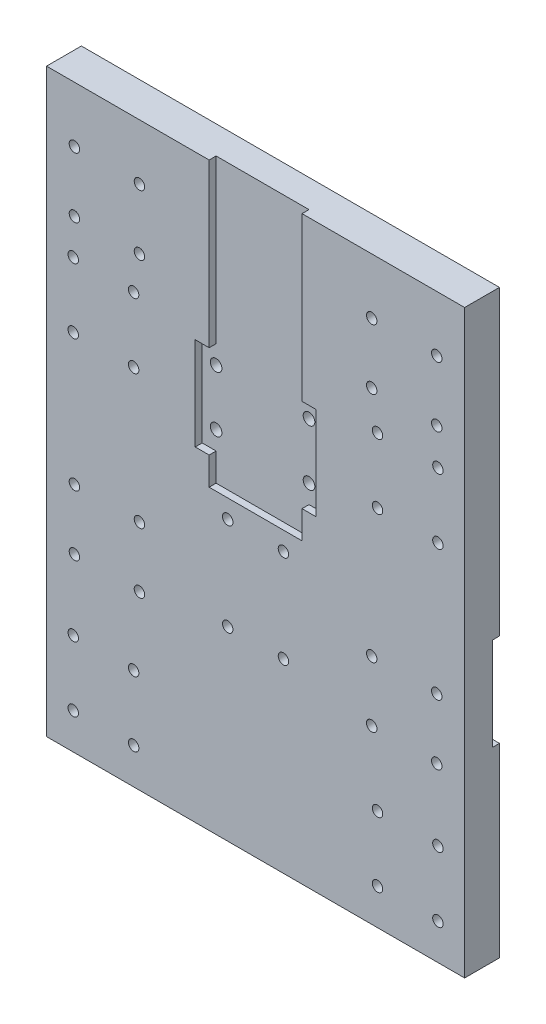
SolidWorks part; units mm, degrees
ref_plane "Plan de face" through (0, 0, 0) normal (0, 0, 1) x (1, 0, 0)
ref_plane "Plan de dessus" through (0, 0, 0) normal (0, 1, 0) x (1, 0, 0)
ref_plane "Plan de droite" through (0, 0, 0) normal (1, 0, 0) x (0, 0, -1)
sketch "Esquisse1" plane through (0, 0, 0) normal (0, 0, 1) x (1, 0, 0)
  line L1 (0, 0) -> (180, 0)
  line L2 (0, 0) -> (0, 250)
  line L3 (0, 250) -> (180, 250)
  line L4 (180, 0) -> (180, 250)
  dimension "D1" = 180
  dimension "D2" = 250
extrude "Boss.-Extru.1" add sketch "Esquisse1" along normal blind 15
sketch "Esquisse2" plane through (0, 0, 15) normal (0, 0, 1) x (1, 0, 0)
  line L0 (90, 0) -> (90, 250) construction
  line L1 (0, 0) -> (180, 0) construction
  line L2 (180, 250) -> (0, 250) construction
  line L3 (180, 100) -> (0, 100) construction
  line L4 (180, 0) -> (180, 250) construction
  line L5 (0, 250) -> (0, 0) construction
  line L6 (11.5, 156.5) -> (37.5, 156.5) construction
  line L7 (37.5, 156.5) -> (37.5, 184.5) construction
  line L8 (37.5, 184.5) -> (11.5, 184.5) construction
  line L9 (11.5, 184.5) -> (11.5, 156.5) construction
  line L10 (168.5, 184.5) -> (168.5, 156.5) construction
  line L11 (142.5, 184.5) -> (168.5, 184.5) construction
  line L12 (142.5, 156.5) -> (142.5, 184.5) construction
  line L13 (168.5, 156.5) -> (142.5, 156.5) construction
  line L14 (168.5, 43.5) -> (142.5, 43.5) construction
  line L15 (142.5, 43.5) -> (142.5, 15.5) construction
  line L16 (142.5, 15.5) -> (168.5, 15.5) construction
  line L17 (168.5, 15.5) -> (168.5, 43.5) construction
  line L18 (11.5, 15.5) -> (11.5, 43.5) construction
  line L19 (37.5, 15.5) -> (11.5, 15.5) construction
  line L20 (37.5, 43.5) -> (37.5, 15.5) construction
  line L21 (11.5, 43.5) -> (37.5, 43.5) construction
  line L39 (11.5, 141.5) -> (11.5, 156.5) construction
  circle A0 centre (11.5, 184.5) radius 2.25
  circle A1 centre (37.5, 184.5) radius 2.25
  circle A2 centre (37.5, 156.5) radius 2.25
  circle A3 centre (11.5, 156.5) radius 2.25
  circle A4 centre (168.5, 156.5) radius 2.25
  circle A5 centre (142.5, 156.5) radius 2.25
  circle A6 centre (142.5, 184.5) radius 2.25
  circle A7 centre (168.5, 184.5) radius 2.25
  circle A8 centre (168.5, 15.5) radius 2.25
  circle A9 centre (142.5, 15.5) radius 2.25
  circle A10 centre (142.5, 43.5) radius 2.25
  circle A11 centre (168.5, 43.5) radius 2.25
  circle A12 centre (11.5, 43.5) radius 2.25
  circle A13 centre (37.5, 43.5) radius 2.25
  circle A14 centre (37.5, 15.5) radius 2.25
  circle A15 centre (11.5, 15.5) radius 2.25
  circle A16 centre (78, 120) radius 2.25
  circle A17 centre (78, 80) radius 2.25
  circle A18 centre (102, 80) radius 2.25
  circle A19 centre (102, 120) radius 2.25
  dimension "D1" = 4.5
  dimension "D2" = 28
  dimension "D3" = 26
  dimension "D7" = 4.5
  dimension "D4" = 105
  dimension "D5" = 113
  dimension "D6" = 150
  dimension "D8" = 15
  dimension "D9" = 24
  dimension "D10" = 40
extrude "Enlèv. mat.-Extru.1" cut sketch "Esquisse2" against normal up to vertex (15 mm away) up to point (0, 250, 0)
sketch "Esquisse3" plane through (0, 0, 15) normal (0, 0, 1) x (1, 0, 0)
  line L0 (90, 0) -> (90, 250) construction
  line L1 (0, 0) -> (180, 0) construction
  line L2 (180, 250) -> (0, 250) construction
  line L3 (0, 150) -> (180, 150) construction
  line L4 (0, 250) -> (0, 0) construction
  line L5 (180, 0) -> (180, 250) construction
  line L6 (40, 200) -> (40, 226) construction
  line L7 (40, 226) -> (12, 226) construction
  line L8 (12, 226) -> (12, 200) construction
  line L9 (12, 200) -> (40, 200) construction
  line L10 (168, 200) -> (140, 200) construction
  line L11 (168, 226) -> (168, 200) construction
  line L12 (140, 226) -> (168, 226) construction
  line L13 (140, 200) -> (140, 226) construction
  line L14 (140, 100) -> (140, 74) construction
  line L15 (140, 74) -> (168, 74) construction
  line L16 (168, 74) -> (168, 100) construction
  line L17 (168, 100) -> (140, 100) construction
  line L18 (12, 100) -> (40, 100) construction
  line L19 (12, 74) -> (12, 100) construction
  line L20 (40, 74) -> (12, 74) construction
  line L21 (40, 100) -> (40, 74) construction
  circle A0 centre (12, 226) radius 2.25
  circle A1 centre (40, 226) radius 2.25
  circle A2 centre (12, 200) radius 2.25
  circle A3 centre (40, 200) radius 2.25
  circle A4 centre (11.5, 156.5) radius 2.25 construction
  circle A5 centre (140, 200) radius 2.25
  circle A6 centre (168, 200) radius 2.25
  circle A7 centre (140, 226) radius 2.25
  circle A8 centre (168, 226) radius 2.25
  circle A9 centre (168, 74) radius 2.25
  circle A10 centre (140, 74) radius 2.25
  circle A11 centre (168, 100) radius 2.25
  circle A12 centre (140, 100) radius 2.25
  circle A13 centre (40, 100) radius 2.25
  circle A14 centre (12, 100) radius 2.25
  circle A15 centre (40, 74) radius 2.25
  circle A16 centre (12, 74) radius 2.25
  dimension "D1" = 28
  dimension "D2" = 26
  dimension "D3" = 50
  dimension "D4" = 100
  dimension "D5" = 50
extrude "Enlèv. mat.-Extru.2" cut sketch "Esquisse3" against normal up to vertex (15 mm away) up to point (180, 250, 0)
sketch "Esquisse6" plane through (0, 0, 0) normal (0, 0, -1) x (-1, 0, 0)
  line L0 (-102, 80) -> (-78, 120) construction
  line L1 (-110, 126) -> (-70, 126)
  line L2 (-110, 126) -> (-110, 74)
  line L3 (-110, 74) -> (-70, 74)
  line L4 (-70, 126) -> (-70, 74)
  line L6 (-90, 74) -> (-90, 0) construction
  line L7 (0, 0) -> (-180, 0) construction
  line L8 (-90, 100) -> (-70, 100) construction
  dimension "D1" = 40
  dimension "D2" = 52
extrude "Enlèv. mat.-Extru.4" cut sketch "Esquisse6" against normal blind 3
sketch "Esquisse4" plane through (0, 0, 0) normal (0, 0, -1) x (-1, 0, 0)
  line L0 (-168.5, 156.5) -> (-168.5, 184.5) construction
  line L1 (-175, 190.5) -> (-136, 190.5)
  line L2 (-175, 190.5) -> (-175, 150.5)
  line L3 (-175, 150.5) -> (-136, 150.5)
  line L4 (-136, 190.5) -> (-136, 150.5)
  line L5 (-168.5, 184.5) -> (-142.5, 184.5) construction
  line L6 (-155.5, 184.5) -> (-155.5, 190.5) construction
  line L7 (-175, 170.5) -> (-168.5, 170.5) construction
  line L8 (-142.5, 156.5) -> (-37.5, 156.5) construction
  line L9 (-142.5, 43.5) -> (-37.5, 43.5) construction
  line L10 (-90, 43.5) -> (-90, 156.5) construction
  line L11 (-90, 100) -> (-121.5, 100) construction
  line L12 (-175, 29.5) -> (-168.5, 29.5) construction
  line L13 (-155.5, 15.5) -> (-155.5, 9.5) construction
  line L14 (-168.5, 15.5) -> (-142.5, 15.5) construction
  line L15 (-168.5, 43.5) -> (-168.5, 15.5) construction
  line L16 (-136, 9.5) -> (-136, 49.5)
  line L17 (-175, 49.5) -> (-136, 49.5)
  line L18 (-175, 9.5) -> (-175, 49.5)
  line L19 (-175, 9.5) -> (-136, 9.5)
  line L20 (-11.5, 43.5) -> (-11.5, 15.5) construction
  line L21 (-11.5, 15.5) -> (-37.5, 15.5) construction
  line L22 (-24.5, 15.5) -> (-24.5, 9.5) construction
  line L23 (-5, 29.5) -> (-11.5, 29.5) construction
  line L24 (-5, 170.5) -> (-11.5, 170.5) construction
  line L25 (-24.5, 184.5) -> (-24.5, 190.5) construction
  line L26 (-11.5, 184.5) -> (-37.5, 184.5) construction
  line L27 (-11.5, 156.5) -> (-11.5, 184.5) construction
  line L28 (-5, 9.5) -> (-44, 9.5)
  line L29 (-5, 9.5) -> (-5, 49.5)
  line L30 (-5, 49.5) -> (-44, 49.5)
  line L31 (-44, 9.5) -> (-44, 49.5)
  line L32 (-44, 190.5) -> (-44, 150.5)
  line L33 (-5, 150.5) -> (-44, 150.5)
  line L34 (-5, 190.5) -> (-5, 150.5)
  line L35 (-5, 190.5) -> (-44, 190.5)
  line L36 (-121.5, 80) -> (-121.5, 120)
  line L37 (-121.5, 120) -> (-109.5, 120)
  line L38 (-109.5, 120) -> (-109.5, 80)
  line L39 (-121.5, 80) -> (-109.5, 80)
  line L40 (-58.5, 80) -> (-70.5, 80)
  line L41 (-70.5, 120) -> (-70.5, 80)
  line L42 (-58.5, 120) -> (-70.5, 120)
  line L43 (-58.5, 80) -> (-58.5, 120)
  point P63 (-109.5, 100)
  point P68 (-70.5, 100)
  dimension "D1" = 39
  dimension "D2" = 40
  dimension "D3" = 40
  dimension "D4" = 12
  dimension "D5" = 19.5
extrude "Enlèv. mat.-Extru.3" cut sketch "Esquisse4" against normal blind 3
sketch "Esquisse7" plane through (0, 0, 15) normal (0, 0, 1) x (1, 0, 0)
  line L1 (90, 160) -> (90, 250) construction
  line L2 (90, 160) -> (0, 160) construction
  line L3 (0, 250) -> (0, 0) construction
  line L4 (180, 250) -> (0, 250) construction
  circle A1 centre (70, 172) radius 2.5
  circle A2 centre (110, 172) radius 2.5
  circle A3 centre (110, 148) radius 2.5
  circle A4 centre (70, 148) radius 2.5
  circle A5 centre (40, 200) radius 2.25 construction
  dimension "D1" = 5
  dimension "D2" = 24
  dimension "D3" = 40
  dimension "D4" = 40
extrude "Enlèv. mat.-Extru.5" cut sketch "Esquisse7" against normal up to vertex
sketch "Esquisse8" plane through (0, 0, 15) normal (0, 0, 1) x (1, 0, 0)
  line L0 (110, 148) -> (70, 172) construction
  line L1 (64, 180) -> (116, 180)
  line L2 (64, 180) -> (64, 140)
  line L3 (64, 140) -> (116, 140)
  line L4 (116, 180) -> (116, 140)
  line L5 (90, 160) -> (90, 180) construction
  line L6 (90, 160) -> (116, 160) construction
  dimension "D1" = 40
  dimension "D2" = 52
extrude "Enlèv. mat.-Extru.6" cut sketch "Esquisse8" against normal blind 3
sketch "Esquisse9" plane through (0, 0, 15) normal (0, 0, 1) x (1, 0, 0)
  line L0 (90, 140) -> (90, 180) construction
  line L1 (70, 128) -> (110, 128)
  line L2 (70, 128) -> (70, 140)
  line L3 (70, 140) -> (110, 140)
  line L4 (110, 128) -> (110, 140)
  line L5 (116, 180) -> (64, 180) construction
  line L6 (64, 140) -> (116, 140) construction
  line L7 (64, 160) -> (116, 160) construction
  line L8 (64, 180) -> (64, 140) construction
  line L9 (116, 140) -> (116, 180) construction
  line L10 (110, 192) -> (110, 180)
  line L11 (70, 180) -> (110, 180)
  line L12 (70, 192) -> (70, 180)
  line L13 (70, 192) -> (110, 192)
  dimension "D1" = 12
  dimension "D2" = 40
extrude "Enlèv. mat.-Extru.7" cut sketch "Esquisse9" against normal blind 3
sketch "Esquisse10" plane through (0, 0, 15) normal (0, 0, 1) x (1, 0, 0)
  line L0 (180, 250) -> (0, 250) construction
  line L1 (70, 250) -> (110, 250)
  line L2 (70, 250) -> (70, 190)
  line L3 (70, 190) -> (110, 190)
  line L4 (110, 250) -> (110, 190)
  line L5 (90, 190) -> (90, 250) construction
  dimension "D1" = 40
  dimension "D2" = 60
extrude "Enlèv. mat.-Extru.8" cut sketch "Esquisse10" against normal blind 3
sketch "Esquisse11" plane through (0, 0, 0) normal (0, 0, -1) x (-1, 0, 0)
  line L0 (0, 250) -> (0, 0) construction
  line L1 (-58.5, 80) -> (0, 80)
  line L2 (-58.5, 80) -> (-58.5, 120)
  line L3 (-58.5, 120) -> (0, 120)
  line L4 (0, 80) -> (0, 120)
  line L6 (-58.5, 120) -> (-70, 120) construction
  line L7 (-180, 0) -> (-180, 250) construction
  line L8 (-121.5, 80) -> (-180, 80)
  line L9 (-121.5, 80) -> (-121.5, 120)
  line L10 (-121.5, 120) -> (-180, 120)
  line L11 (-180, 80) -> (-180, 120)
  line L12 (-110, 120) -> (-121.5, 120) construction
extrude "Enlèv. mat.-Extru.9" cut sketch "Esquisse11" against normal up to vertex (3 mm away) up to point (70, 120, 3)
